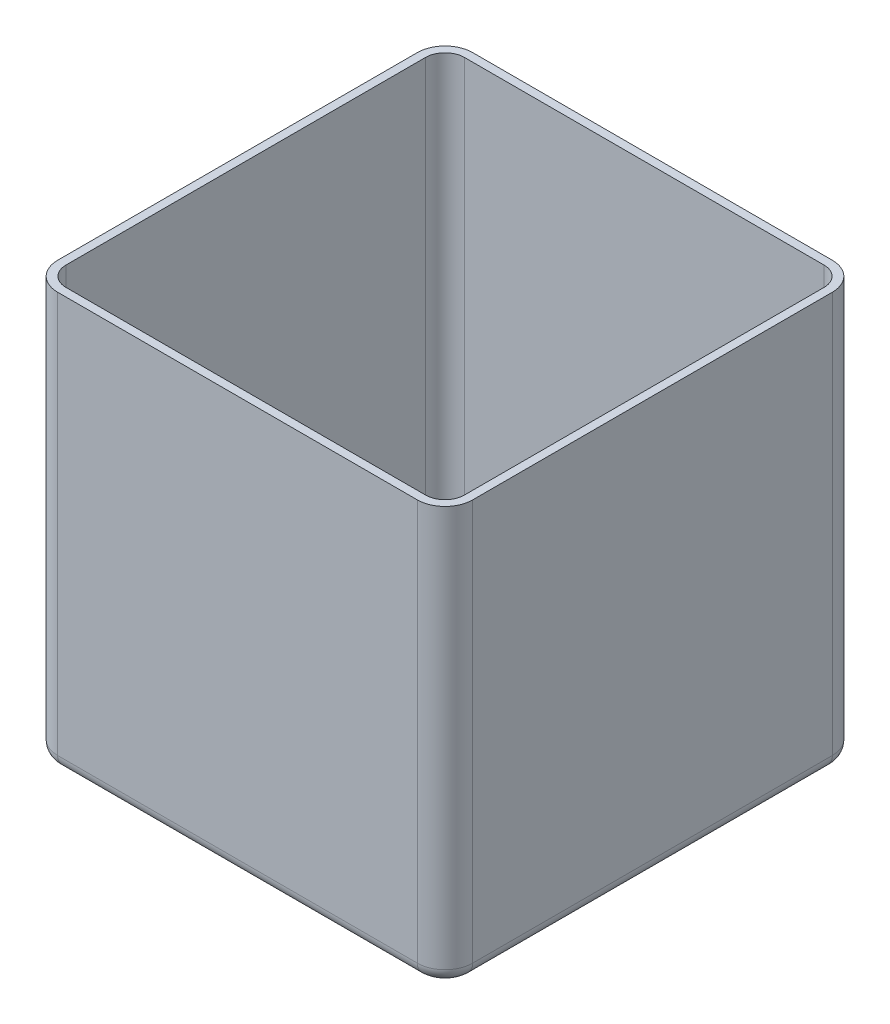
SolidWorks part; units mm, degrees
ref_plane "Alzado" through (0, 0, 0) normal (0, 0, 1) x (1, 0, 0)
ref_plane "Planta" through (0, 0, 0) normal (0, 1, 0) x (1, 0, 0)
ref_plane "Vista lateral" through (0, 0, 0) normal (1, 0, 0) x (0, 0, -1)
sketch "Croquis1" plane through (0, 0, 0) normal (0, 1, 0) x (1, 0, 0)
  line L1 (75, -75) -> (-75, -75)
  line L2 (75, -75) -> (75, 75)
  line L3 (75, 75) -> (-75, 75)
  line L4 (-75, -75) -> (-75, 75)
  line L5 (75, -75) -> (-75, 75) construction
  line L6 (75, 75) -> (-75, -75) construction
  point P0 (0, 0)
  dimension "D1" = 150
  dimension "D2" = 150
extrude "Extruir1" add sketch "Croquis1" against normal blind 150
fillet "Redondeo1" radius 10 4 edges at (-75, -75, 75) (-75, -75, -75) (75, -75, 75) (75, -75, -75)
fillet "Redondeo2" radius 5 8 edges at (72.0711, -150, 72.0711) (75, -150, 0) (72.0711, -150, -72.0711) (0, -150, -75) (-72.0711, -150, -72.0711) (-75, -150, 0) (-72.0711, -150, 72.0711) (0, -150, 75)
shell "Vaciado1" thickness 3
